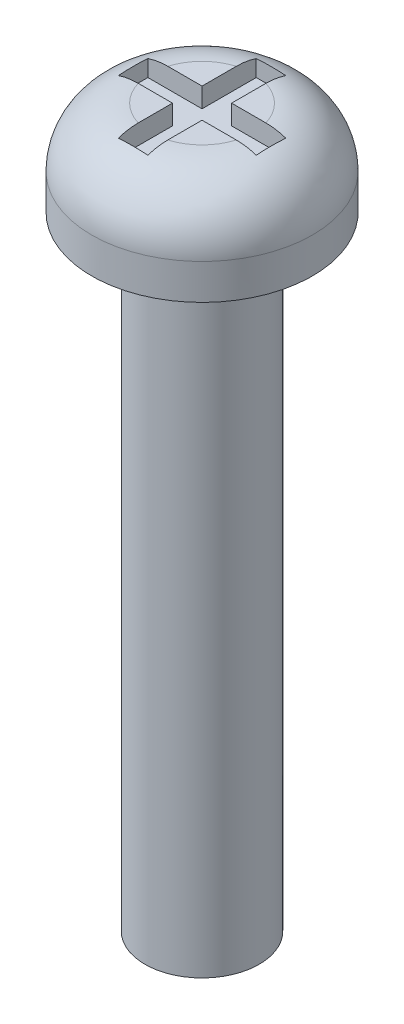
SolidWorks part; units mm, degrees
ref_plane "Front Plane" through (0, 0, 0) normal (0, 0, 1) x (1, 0, 0)
ref_plane "Top Plane" through (0, 0, 0) normal (0, 1, 0) x (1, 0, 0)
ref_plane "Right Plane" through (0, 0, 0) normal (1, 0, 0) x (0, 0, -1)
sketch "Sketch1" plane through (0, 0, 0) normal (0, 0, 1) x (1, 0, 0)
  line L0 (0, 0) -> (0, 98.3537) construction
  line L1 (0, 18.4) -> (2.8, 18.4)
  line L2 (1.45, 16) -> (2.8, 16)
  line L3 (0, 0) -> (1, 0)
  line L4 (1.45, 16) -> (1.45, 0.2)
  line L5 (1, 0) -> (1.45, 0.2)
  line L6 (0, 0) -> (0, 18.4)
  line L7 (2.8, 16) -> (2.8, 18.4)
  dimension "D1" = 5.6
  dimension "D2" = 2.9
  dimension "D3" = 2.4
  dimension "D4" = 16
  dimension "D5" = 1
  dimension "D6" = 0.2
revolve "Revolve1" add sketch "Sketch1" angle 360 about L0
fillet "Fillet1" radius 1.5 1 edges at (0, 18.4, -2.8)
sketch "Sketch2" plane through (0, 18.4, 0) normal (0, 1, 0) x (1, 0, 0)
  line L0 (0, 0) -> (0, 2.0772) construction
  line L1 (1.75, 0.375) -> (1.75, -0.375)
  line L2 (-0.375, 1.75) -> (0.375, 1.75)
  line L3 (-0.375, 1.75) -> (-0.375, 0.375)
  line L5 (0.375, 1.75) -> (0.375, 0.375)
  line L6 (1.75, 0.375) -> (0.375, 0.375)
  line L8 (1.75, -0.375) -> (0.375, -0.375)
  line L9 (0.375, -1.75) -> (-0.375, -1.75)
  line L10 (0.375, -1.75) -> (0.375, -0.375)
  line L12 (-0.375, -1.75) -> (-0.375, -0.375)
  line L13 (-1.75, -0.375) -> (-1.75, 0.375)
  line L14 (-1.75, -0.375) -> (-0.375, -0.375)
  line L16 (-1.75, 0.375) -> (-0.375, 0.375)
  point P22 (0, 0)
  dimension "D1" = 0.75
  dimension "D2" = 1.75
  dimension "D3" = 4
extrude "Cut-Extrude1" cut sketch "Sketch2" against normal blind 0.5
